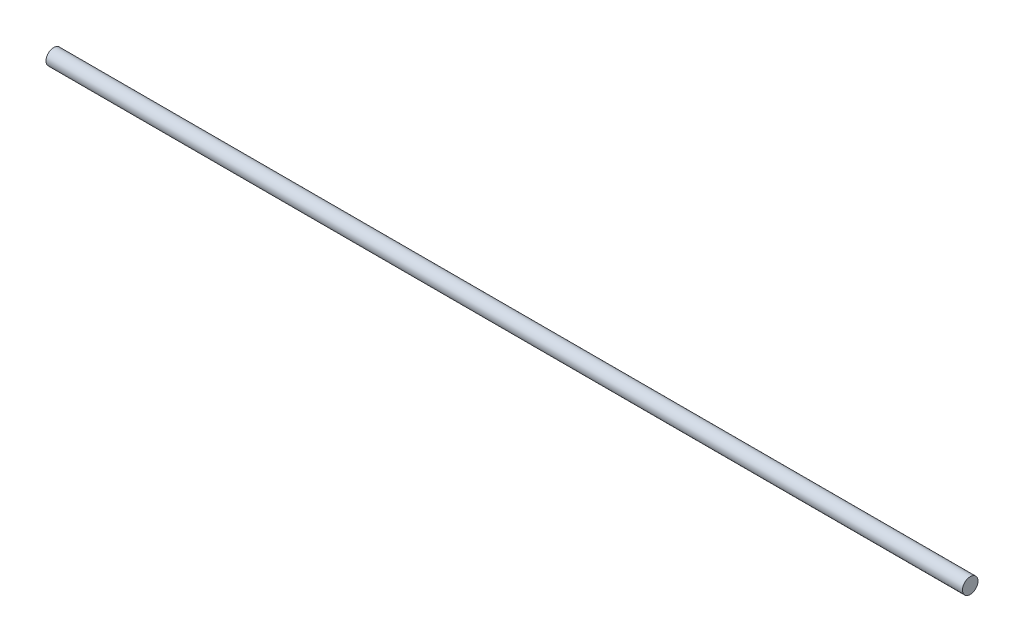
SolidWorks part; units mm, degrees
ref_plane "Front Plane" through (0, 0, 0) normal (0, 0, 1) x (1, 0, 0)
ref_plane "Top Plane" through (0, 0, 0) normal (0, 1, 0) x (1, 0, 0)
ref_plane "Right Plane" through (0, 0, 0) normal (1, 0, 0) x (0, 0, -1)
sketch "Sketch1" plane through (0, 0, 0) normal (1, 0, 0) x (0, 0, -1)
  circle A0 centre (0, 0) radius 5
  dimension "D1" = 10
extrude "Boss-Extrude1" add sketch "Sketch1" along normal blind 590
